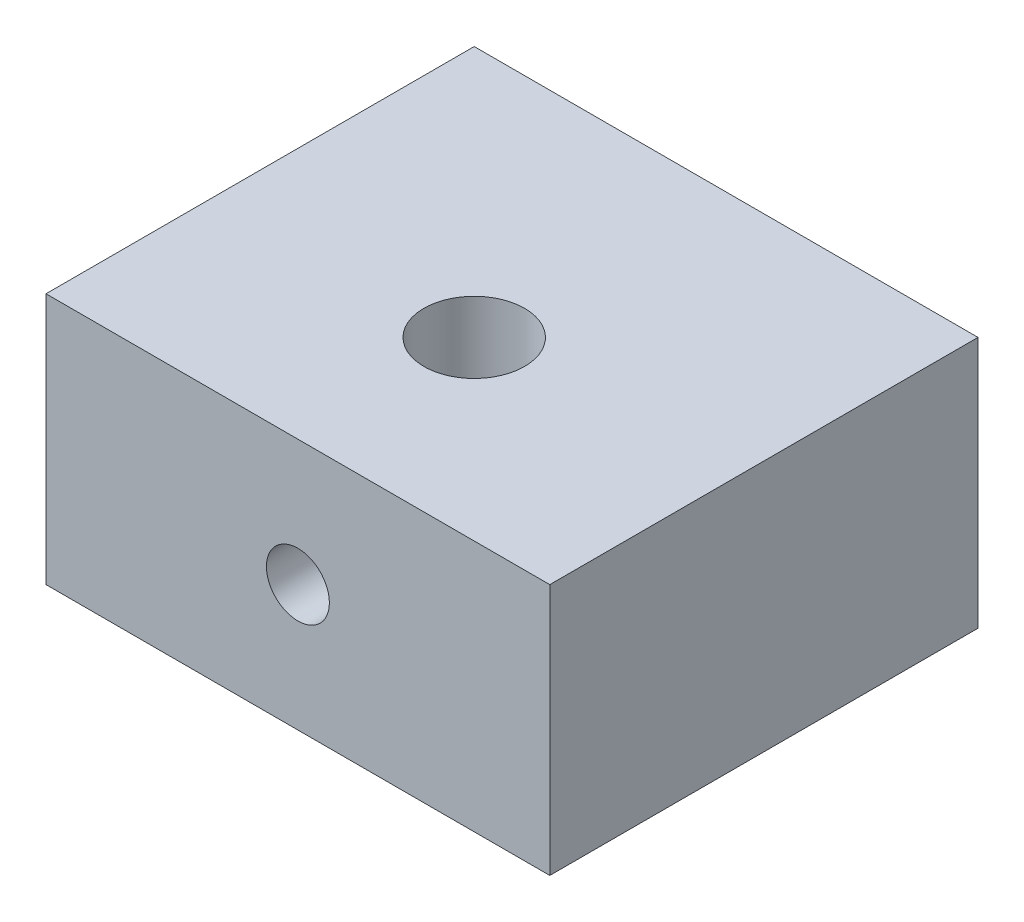
SolidWorks part; units mm, degrees
material "2024-T3"
ref_plane "正面" through (0, 0, 0) normal (0, 0, 1) x (1, 0, 0)
ref_plane "平面" through (0, 0, 0) normal (0, 1, 0) x (1, 0, 0)
ref_plane "右側面" through (0, 0, 0) normal (1, 0, 0) x (0, 0, -1)
sketch "ｽｹｯﾁ1" plane through (0, 0, 0) normal (0, 0, 1) x (1, 0, 0)
  line L1 (0, 0) -> (20, 0)
  line L2 (0, 0) -> (0, 10)
  line L3 (0, 10) -> (20, 10)
  line L4 (20, 0) -> (20, 10)
  dimension "D1" = 10
  dimension "D2" = 20
extrude "ﾎﾞｽ - 押し出し1" add sketch "ｽｹｯﾁ1" along normal blind 17
sketch "ｽｹｯﾁ2" plane through (0, 0, 0) normal (0, -1, 0) x (1, 0, 0)
  line L0 (0, 17) -> (0, 0) construction
  line L1 (0, 17) -> (20, 17) construction
  circle A0 centre (10, 10) radius 2
  dimension "D1" = 10
  dimension "D3" = 4
  dimension "D2" = 7
extrude "ｶｯﾄ - 押し出し1" cut sketch "ｽｹｯﾁ2" against normal through all
sketch "ｽｹｯﾁ3" plane through (0, 0, 0) normal (0, 0, -1) x (-1, 0, 0)
  line L0 (-20, 5) -> (0, 5)
  line L1 (-20, 0) -> (-20, 10) construction
  line L2 (0, 10) -> (0, 0) construction
  point P6 (-15, 5)
  point P7 (-5, 5)
  dimension "D1" = 5
  dimension "D2" = 5
  dimension "D4" = 5
hole_wizard "M3x0.5 ねじ穴1" positions "ｽｹｯﾁ3" profile "ｽｹｯﾁ4" tap size "M3x0.5" standard "JIS"
sketch "ｽｹｯﾁ4" plane through (5, 5, 0) normal (1, 0, 0) x (0, 1, 0)
  line L0 (0, 0) -> (0, 13.2511)
  line L1 (0, 13.2511) -> (1.25, 12.5)
  line L2 (1.25, 12.5) -> (1.25, 0)
  line L5 (1.25, 0) -> (0, 0)
  line L10 (0, 13.2511) -> (-1.25, 12.5) construction
  line L11 (0, -6.35) -> (0, 107.95) construction
  dimension "ねじ下穴ﾄﾞﾘﾙ直径" = 2.5
  dimension "ねじ下穴ﾄﾞﾘﾙの深さ" = 12.5
  dimension "ﾄﾞﾘﾙ角度" = 118
cosmetic thread "穴のねじ山1" parameters "D1"=10, "D2"=3
cosmetic thread "穴のねじ山2" parameters "D1"=10, "D2"=3
sketch "ｽｹｯﾁ5" plane through (0, 0, 17) normal (0, 0, 1) x (1, 0, 0)
  line L0 (20, 10) -> (0, 10) construction
  line L1 (0, 10) -> (0, 0) construction
  point P0 (10, 5)
  dimension "D1" = 5
  dimension "D2" = 10
hole_wizard "M3x0.5 ねじ穴2" positions "ｽｹｯﾁ5" profile "ｽｹｯﾁ6" tap size "M3x0.5" standard "JIS"
sketch "ｽｹｯﾁ6" plane through (10, 5, 17) normal (1, 0, 0) x (0, -1, 0)
  line L0 (0, 0) -> (0, 5)
  line L1 (0, 5) -> (1.25, 5)
  line L2 (1.25, 5) -> (1.25, 0)
  line L5 (1.25, 0) -> (0, 0)
  line L11 (0, -6.35) -> (0, 107.95) construction
  dimension "次ｻｰﾌｪｽまでのねじ下穴ﾄﾞﾘﾙ直径" = 2.5
  dimension "次ｻｰﾌｪｽまでのねじ下穴ﾄﾞﾘﾙの深さ" = 5
cosmetic thread "穴のねじ山3" parameters "D2"=3
